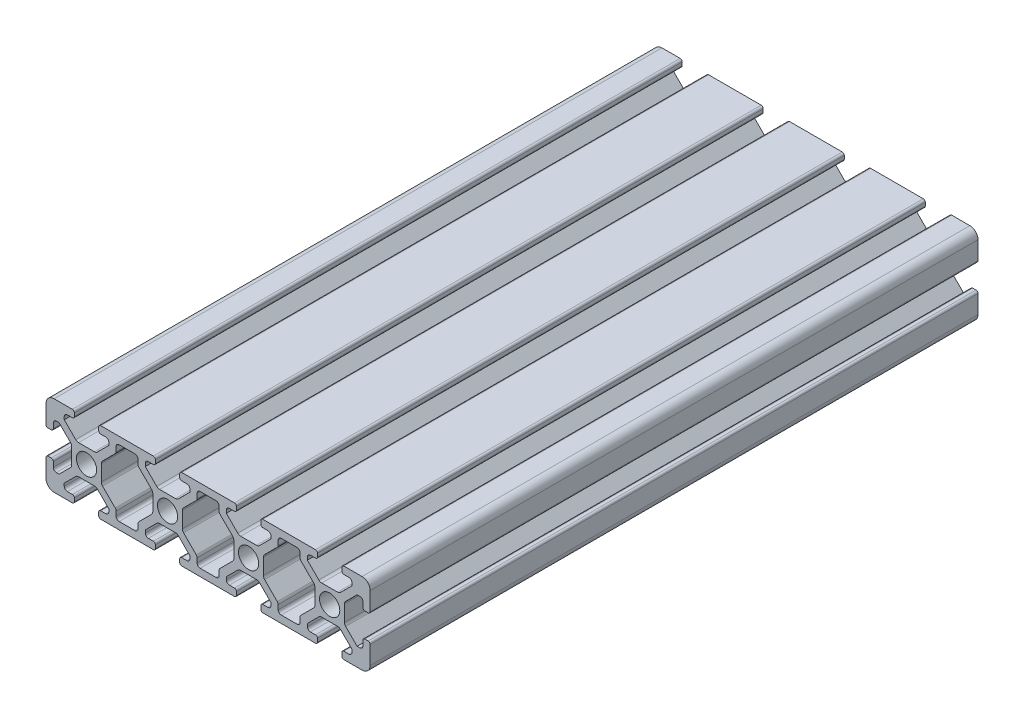
SolidWorks part; units mm, degrees
material "6063-T5"
ref_plane "Front Plane" through (0, 0, 0) normal (0, 0, 1) x (1, 0, 0)
ref_plane "Top Plane" through (0, 0, 0) normal (0, 1, 0) x (1, 0, 0)
ref_plane "Right Plane" through (0, 0, 0) normal (1, 0, 0) x (0, 0, -1)
sketch "Sketch1" plane through (0, 0, 0) normal (0, 0, 1) x (1, 0, 0)
  line L0 (-41.935, 2.3415) -> (-37.435, 2.3415)
  line L1 (36.065, 4.3415) -> (36.065, 8.8415)
  line L2 (34.065, 22.3415) -> (29.565, 22.3415)
  line L3 (-43.935, 20.3415) -> (-43.935, 15.8415)
  line L4 (-10.935, 21.8415) -> (-10.935, 21.0415)
  line L5 (-16.935, 21.8415) -> (-16.935, 21.0415)
  line L6 (-36.935, 21.8415) -> (-36.935, 21.0415)
  line L7 (-30.935, 21.8415) -> (-30.935, 21.0415)
  line L8 (-37.435, 22.3415) -> (-41.935, 22.3415)
  line L9 (9.065, 21.8415) -> (9.065, 21.0415)
  line L10 (3.065, 21.8415) -> (3.065, 21.0415)
  line L11 (29.065, 21.8415) -> (29.065, 21.0415)
  line L12 (23.065, 21.8415) -> (23.065, 21.0415)
  line L13 (-10.935, 3.6415) -> (-10.935, 2.8415)
  line L14 (-16.935, 3.6415) -> (-16.935, 2.8415)
  line L15 (9.065, 3.6415) -> (9.065, 2.8415)
  line L16 (3.065, 3.6415) -> (3.065, 2.8415)
  line L17 (29.065, 3.6415) -> (29.065, 2.8415)
  line L18 (23.065, 3.6415) -> (23.065, 2.8415)
  line L19 (-30.935, 3.6415) -> (-30.935, 2.8415)
  line L20 (-36.935, 3.6415) -> (-36.935, 2.8415)
  line L21 (-30.435, 22.3415) -> (-17.435, 22.3415) construction
  line L22 (-17.435, 22.3415) -> (-30.435, 22.3415)
  line L23 (2.565, 22.3415) -> (-10.435, 22.3415)
  line L24 (22.565, 22.3415) -> (9.565, 22.3415)
  line L25 (29.565, 2.3415) -> (34.065, 2.3415)
  line L26 (9.565, 2.3415) -> (22.565, 2.3415)
  line L27 (-10.435, 2.3415) -> (2.565, 2.3415)
  line L28 (-30.435, 2.3415) -> (-17.435, 2.3415)
  line L29 (35.565, 15.3415) -> (34.765, 15.3415)
  line L30 (35.565, 9.3415) -> (34.765, 9.3415)
  line L31 (-43.435, 15.3415) -> (-42.635, 15.3415)
  line L32 (-43.435, 9.3415) -> (-42.635, 9.3415)
  line L33 (-43.935, 8.8415) -> (-43.935, 4.3415)
  line L34 (36.065, 15.8415) -> (36.065, 20.3415)
  line L35 (-42.135, 15.8415) -> (-42.135, 17.0915)
  line L36 (-38.685, 20.5415) -> (-37.435, 20.5415)
  line L37 (34.265, 17.0915) -> (34.265, 15.8415)
  line L38 (30.815, 4.1415) -> (29.565, 4.1415)
  line L39 (-42.135, 7.5915) -> (-42.135, 8.8415)
  line L40 (-30.435, 20.5415) -> (-29.185, 20.5415)
  line L41 (-37.435, 4.1415) -> (-38.685, 4.1415)
  line L42 (-10.435, 20.5415) -> (-9.185, 20.5415)
  line L43 (-17.435, 4.1415) -> (-18.685, 4.1415)
  line L44 (9.565, 20.5415) -> (10.815, 20.5415)
  line L45 (2.565, 4.1415) -> (1.315, 4.1415)
  line L46 (29.565, 20.5415) -> (30.815, 20.5415)
  line L47 (22.565, 4.1415) -> (21.315, 4.1415)
  line L48 (34.265, 8.8415) -> (34.265, 7.5915)
  line L49 (-31.2649, 16.2843) -> (-28.435, 19.1142)
  line L50 (-31.2649, 8.3986) -> (-28.435, 5.5687)
  line L51 (-11.2649, 16.2843) -> (-8.435, 19.1142)
  line L52 (-9.9921, 15.0116) -> (-6.8546, 18.149)
  line L53 (-16.6051, 16.2843) -> (-19.435, 19.1142)
  line L54 (-21.0153, 18.149) -> (-17.8778, 15.0116)
  line L55 (-16.6051, 8.3986) -> (-19.435, 5.5687)
  line L56 (-21.0153, 6.5339) -> (-17.8778, 9.6714)
  line L57 (3.3949, 16.2843) -> (0.565, 19.1142)
  line L58 (-1.0153, 18.149) -> (2.1222, 15.0116)
  line L59 (3.3949, 8.3986) -> (0.565, 5.5687)
  line L60 (-1.0153, 6.5339) -> (2.1222, 9.6714)
  line L61 (23.3949, 16.2843) -> (20.565, 19.1142)
  line L62 (18.9847, 18.149) -> (22.1222, 15.0116)
  line L63 (23.3949, 8.3986) -> (20.565, 5.5687)
  line L64 (18.9847, 6.5339) -> (22.1222, 9.6714)
  line L65 (-9.9921, 9.6714) -> (-6.8546, 6.5339)
  line L66 (-29.9921, 15.0116) -> (-26.8546, 18.149)
  line L67 (-37.8778, 9.6714) -> (-40.7077, 6.8415)
  line L68 (-36.6051, 8.3986) -> (-39.435, 5.5687)
  line L69 (-36.6051, 16.2843) -> (-39.435, 19.1142)
  line L70 (-11.2649, 8.3986) -> (-8.435, 5.5687)
  line L71 (-29.9921, 9.6714) -> (-26.8546, 6.5339)
  line L72 (8.7351, 16.2843) -> (11.565, 19.1142)
  line L73 (-37.8778, 15.0116) -> (-40.7077, 17.8415)
  line L74 (10.0079, 15.0116) -> (13.1454, 18.149)
  line L75 (10.0079, 9.6714) -> (13.1454, 6.5339)
  line L76 (8.7351, 8.3986) -> (11.565, 5.5687)
  line L77 (28.7351, 16.2843) -> (31.565, 19.1142)
  line L78 (30.0079, 15.0116) -> (32.8378, 17.8415)
  line L79 (30.0079, 9.6714) -> (32.8378, 6.8415)
  line L80 (28.7351, 8.3986) -> (31.565, 5.5687)
  line L81 (-15.898, 15.9915) -> (-11.972, 15.9915)
  line L82 (-25.885, 20.5415) -> (-21.985, 20.5415)
  line L83 (-29.185, 4.1415) -> (-30.435, 4.1415)
  line L84 (-28.435, 19.7915) -> (-28.435, 19.1142)
  line L85 (-9.185, 4.1415) -> (-10.435, 4.1415)
  line L86 (-39.435, 19.7915) -> (-39.435, 19.1142)
  line L87 (10.815, 4.1415) -> (9.565, 4.1415)
  line L88 (-19.435, 19.7915) -> (-19.435, 19.1142)
  line L89 (-18.685, 20.5415) -> (-17.435, 20.5415)
  line L90 (1.315, 20.5415) -> (2.565, 20.5415)
  line L91 (-10.285, 14.3044) -> (-10.285, 10.3785)
  line L92 (-11.972, 8.6915) -> (-15.898, 8.6915)
  line L93 (-17.585, 10.3785) -> (-17.585, 14.3044)
  line L94 (21.315, 20.5415) -> (22.565, 20.5415)
  line L95 (0.565, 19.7915) -> (0.565, 19.1142)
  line L96 (-8.435, 19.7915) -> (-8.435, 19.1142)
  line L97 (-30.285, 14.3044) -> (-30.285, 10.3785)
  line L98 (-31.972, 8.6915) -> (-35.898, 8.6915)
  line L99 (-37.585, 10.3785) -> (-37.585, 14.3044)
  line L100 (-35.898, 15.9915) -> (-31.972, 15.9915)
  line L101 (4.102, 15.9915) -> (8.028, 15.9915)
  line L102 (9.715, 14.3044) -> (9.715, 10.3785)
  line L103 (8.028, 8.6915) -> (4.102, 8.6915)
  line L104 (2.415, 10.3785) -> (2.415, 14.3044)
  line L105 (24.102, 15.9915) -> (28.028, 15.9915)
  line L106 (29.715, 14.3044) -> (29.715, 10.3785)
  line L107 (28.028, 8.6915) -> (24.102, 8.6915)
  line L108 (22.415, 10.3785) -> (22.415, 14.3044)
  line L109 (20.565, 19.7915) -> (20.565, 19.1142)
  line L110 (11.565, 19.7915) -> (11.565, 19.1142)
  line L111 (-39.435, 4.8915) -> (-39.435, 5.5687)
  line L112 (31.565, 19.7915) -> (31.565, 19.1142)
  line L113 (-19.435, 4.8915) -> (-19.435, 5.5687)
  line L114 (-28.435, 4.8915) -> (-28.435, 5.5687)
  line L115 (0.565, 4.8915) -> (0.565, 5.5687)
  line L116 (-8.435, 4.8915) -> (-8.435, 5.5687)
  line L117 (20.565, 4.8915) -> (20.565, 5.5687)
  line L118 (11.565, 4.8915) -> (11.565, 5.5687)
  line L119 (-41.385, 17.8415) -> (-40.7077, 17.8415)
  line L120 (31.565, 4.8915) -> (31.565, 5.5687)
  line L121 (-41.385, 6.8415) -> (-40.7077, 6.8415)
  line L122 (33.515, 17.8415) -> (32.8378, 17.8415)
  line L123 (-26.635, 19.7915) -> (-26.635, 18.6793)
  line L124 (33.515, 6.8415) -> (32.8378, 6.8415)
  line L125 (-21.235, 19.7915) -> (-21.235, 18.6793)
  line L126 (-5.885, 20.5415) -> (-1.985, 20.5415)
  line L127 (-6.635, 19.7915) -> (-6.635, 18.6793)
  line L128 (-1.235, 19.7915) -> (-1.235, 18.6793)
  line L129 (14.115, 20.5415) -> (18.015, 20.5415)
  line L130 (13.365, 19.7915) -> (13.365, 18.6793)
  line L131 (18.765, 19.7915) -> (18.765, 18.6793)
  line L132 (-26.635, 6.0036) -> (-26.635, 4.8915)
  line L133 (-25.885, 4.1415) -> (-21.985, 4.1415)
  line L134 (-21.235, 4.8915) -> (-21.235, 6.0036)
  line L135 (-6.635, 6.0036) -> (-6.635, 4.8915)
  line L136 (-5.885, 4.1415) -> (-1.985, 4.1415)
  line L137 (-1.235, 4.8915) -> (-1.235, 6.0036)
  line L138 (13.365, 6.0036) -> (13.365, 4.8915)
  line L139 (14.115, 4.1415) -> (18.015, 4.1415)
  line L140 (18.765, 4.8915) -> (18.765, 6.0036)
  circle A0 centre (-33.935, 12.3415) radius 2.5
  circle A1 centre (-13.935, 12.3415) radius 2.5
  circle A2 centre (6.065, 12.3415) radius 2.5
  circle A3 centre (26.065, 12.3415) radius 2.5
  arc A4 (34.065, 2.3415) -> (36.065, 4.3415) centre (34.065, 4.3415) ccw
  arc A5 (36.065, 20.3415) -> (34.065, 22.3415) centre (34.065, 20.3415) ccw
  arc A6 (-41.935, 2.3415) -> (-43.935, 4.3415) centre (-41.935, 4.3415) cw
  arc A7 (-41.935, 22.3415) -> (-43.935, 20.3415) centre (-41.935, 20.3415) ccw
  arc A8 (-31.2649, 16.2843) -> (-31.972, 15.9915) centre (-31.972, 16.9915) cw
  arc A9 (-36.6051, 16.2843) -> (-35.898, 15.9915) centre (-35.898, 16.9915) ccw
  arc A10 (-37.8778, 15.0116) -> (-37.585, 14.3044) centre (-38.585, 14.3044) cw
  arc A11 (-37.8778, 9.6714) -> (-37.585, 10.3785) centre (-38.585, 10.3785) ccw
  arc A12 (-36.6051, 8.3986) -> (-35.898, 8.6915) centre (-35.898, 7.6915) cw
  arc A13 (-31.2649, 8.3986) -> (-31.972, 8.6915) centre (-31.972, 7.6915) ccw
  arc A14 (-11.2649, 8.3986) -> (-11.972, 8.6915) centre (-11.972, 7.6915) ccw
  arc A15 (-16.6051, 8.3986) -> (-15.898, 8.6915) centre (-15.898, 7.6915) cw
  arc A16 (-16.6051, 16.2843) -> (-15.898, 15.9915) centre (-15.898, 16.9915) ccw
  arc A17 (-11.2649, 16.2843) -> (-11.972, 15.9915) centre (-11.972, 16.9915) cw
  arc A18 (3.3949, 8.3986) -> (4.102, 8.6915) centre (4.102, 7.6915) cw
  arc A19 (8.7351, 8.3986) -> (8.028, 8.6915) centre (8.028, 7.6915) ccw
  arc A20 (8.7351, 16.2843) -> (8.028, 15.9915) centre (8.028, 16.9915) cw
  arc A21 (3.3949, 16.2843) -> (4.102, 15.9915) centre (4.102, 16.9915) ccw
  arc A22 (28.7351, 16.2843) -> (28.028, 15.9915) centre (28.028, 16.9915) cw
  arc A23 (23.3949, 16.2843) -> (24.102, 15.9915) centre (24.102, 16.9915) ccw
  arc A24 (23.3949, 8.3986) -> (24.102, 8.6915) centre (24.102, 7.6915) cw
  arc A25 (28.7351, 8.3986) -> (28.028, 8.6915) centre (28.028, 7.6915) ccw
  arc A26 (30.0079, 9.6714) -> (29.715, 10.3785) centre (30.715, 10.3785) cw
  arc A27 (30.0079, 15.0116) -> (29.715, 14.3044) centre (30.715, 14.3044) ccw
  arc A28 (22.1222, 9.6714) -> (22.415, 10.3785) centre (21.415, 10.3785) ccw
  arc A29 (22.1222, 15.0116) -> (22.415, 14.3044) centre (21.415, 14.3044) cw
  arc A30 (10.0079, 9.6714) -> (9.715, 10.3785) centre (10.715, 10.3785) cw
  arc A31 (10.0079, 15.0116) -> (9.715, 14.3044) centre (10.715, 14.3044) ccw
  arc A32 (34.265, 17.0915) -> (33.515, 17.8415) centre (33.515, 17.0915) ccw
  arc A33 (31.565, 19.7915) -> (30.815, 20.5415) centre (30.815, 19.7915) ccw
  arc A34 (34.265, 7.5915) -> (33.515, 6.8415) centre (33.515, 7.5915) cw
  arc A35 (31.565, 4.8915) -> (30.815, 4.1415) centre (30.815, 4.8915) cw
  arc A36 (2.1222, 9.6714) -> (2.415, 10.3785) centre (1.415, 10.3785) ccw
  arc A37 (2.1222, 15.0116) -> (2.415, 14.3044) centre (1.415, 14.3044) cw
  arc A38 (-9.9921, 9.6714) -> (-10.285, 10.3785) centre (-9.285, 10.3785) cw
  arc A39 (-9.9921, 15.0116) -> (-10.285, 14.3044) centre (-9.285, 14.3044) ccw
  arc A40 (-29.9921, 15.0116) -> (-30.285, 14.3044) centre (-29.285, 14.3044) ccw
  arc A41 (-29.9921, 9.6714) -> (-30.285, 10.3785) centre (-29.285, 10.3785) cw
  arc A42 (-17.8778, 9.6714) -> (-17.585, 10.3785) centre (-18.585, 10.3785) ccw
  arc A43 (-17.8778, 15.0116) -> (-17.585, 14.3044) centre (-18.585, 14.3044) cw
  arc A44 (21.315, 4.1415) -> (20.565, 4.8915) centre (21.315, 4.8915) cw
  arc A45 (18.015, 4.1415) -> (18.765, 4.8915) centre (18.015, 4.8915) ccw
  arc A46 (13.365, 4.8915) -> (14.115, 4.1415) centre (14.115, 4.8915) ccw
  arc A47 (10.815, 4.1415) -> (11.565, 4.8915) centre (10.815, 4.8915) ccw
  arc A48 (1.315, 4.1415) -> (0.565, 4.8915) centre (1.315, 4.8915) cw
  arc A49 (20.565, 19.7915) -> (21.315, 20.5415) centre (21.315, 19.7915) cw
  arc A50 (18.015, 20.5415) -> (18.765, 19.7915) centre (18.015, 19.7915) cw
  arc A51 (14.115, 20.5415) -> (13.365, 19.7915) centre (14.115, 19.7915) ccw
  arc A52 (9.065, 21.0415) -> (9.565, 20.5415) centre (9.565, 21.0415) ccw
  arc A53 (9.065, 21.8415) -> (9.565, 22.3415) centre (9.565, 21.8415) cw
  arc A54 (23.065, 21.0415) -> (22.565, 20.5415) centre (22.565, 21.0415) cw
  arc A55 (23.065, 21.8415) -> (22.565, 22.3415) centre (22.565, 21.8415) ccw
  arc A56 (29.065, 21.0415) -> (29.565, 20.5415) centre (29.565, 21.0415) ccw
  arc A57 (29.065, 21.8415) -> (29.565, 22.3415) centre (29.565, 21.8415) cw
  arc A58 (34.765, 15.3415) -> (34.265, 15.8415) centre (34.765, 15.8415) cw
  arc A59 (35.565, 15.3415) -> (36.065, 15.8415) centre (35.565, 15.8415) ccw
  arc A60 (34.765, 9.3415) -> (34.265, 8.8415) centre (34.765, 8.8415) ccw
  arc A61 (35.565, 9.3415) -> (36.065, 8.8415) centre (35.565, 8.8415) cw
  arc A62 (29.065, 2.8415) -> (29.565, 2.3415) centre (29.565, 2.8415) ccw
  arc A63 (29.065, 3.6415) -> (29.565, 4.1415) centre (29.565, 3.6415) cw
  arc A64 (23.065, 2.8415) -> (22.565, 2.3415) centre (22.565, 2.8415) cw
  arc A65 (23.065, 3.6415) -> (22.565, 4.1415) centre (22.565, 3.6415) ccw
  arc A66 (9.065, 2.8415) -> (9.565, 2.3415) centre (9.565, 2.8415) ccw
  arc A67 (9.065, 3.6415) -> (9.565, 4.1415) centre (9.565, 3.6415) cw
  arc A68 (3.065, 2.8415) -> (2.565, 2.3415) centre (2.565, 2.8415) cw
  arc A69 (3.065, 3.6415) -> (2.565, 4.1415) centre (2.565, 3.6415) ccw
  arc A70 (-10.935, 2.8415) -> (-10.435, 2.3415) centre (-10.435, 2.8415) ccw
  arc A71 (-10.935, 3.6415) -> (-10.435, 4.1415) centre (-10.435, 3.6415) cw
  arc A72 (-16.935, 2.8415) -> (-17.435, 2.3415) centre (-17.435, 2.8415) cw
  arc A73 (-16.935, 3.6415) -> (-17.435, 4.1415) centre (-17.435, 3.6415) ccw
  arc A74 (3.065, 21.0415) -> (2.565, 20.5415) centre (2.565, 21.0415) cw
  arc A75 (3.065, 21.8415) -> (2.565, 22.3415) centre (2.565, 21.8415) ccw
  arc A76 (-10.935, 21.0415) -> (-10.435, 20.5415) centre (-10.435, 21.0415) ccw
  arc A77 (-10.935, 21.8415) -> (-10.435, 22.3415) centre (-10.435, 21.8415) cw
  arc A78 (-16.935, 21.0415) -> (-17.435, 20.5415) centre (-17.435, 21.0415) cw
  arc A79 (-16.935, 21.8415) -> (-17.435, 22.3415) centre (-17.435, 21.8415) ccw
  arc A80 (-30.935, 21.0415) -> (-30.435, 20.5415) centre (-30.435, 21.0415) ccw
  arc A81 (-30.435, 22.3415) -> (-30.935, 21.8415) centre (-30.435, 21.8415) ccw
  arc A82 (-30.935, 2.8415) -> (-30.435, 2.3415) centre (-30.435, 2.8415) ccw
  arc A83 (-30.935, 3.6415) -> (-30.435, 4.1415) centre (-30.435, 3.6415) cw
  arc A84 (-36.935, 2.8415) -> (-37.435, 2.3415) centre (-37.435, 2.8415) cw
  arc A85 (-36.935, 3.6415) -> (-37.435, 4.1415) centre (-37.435, 3.6415) ccw
  arc A86 (-43.935, 8.8415) -> (-43.435, 9.3415) centre (-43.435, 8.8415) cw
  arc A87 (-42.635, 9.3415) -> (-42.135, 8.8415) centre (-42.635, 8.8415) cw
  arc A88 (-43.935, 15.8415) -> (-43.435, 15.3415) centre (-43.435, 15.8415) ccw
  arc A89 (-42.635, 15.3415) -> (-42.135, 15.8415) centre (-42.635, 15.8415) ccw
  arc A90 (-37.435, 22.3415) -> (-36.935, 21.8415) centre (-37.435, 21.8415) cw
  arc A91 (-36.935, 21.0415) -> (-37.435, 20.5415) centre (-37.435, 21.0415) cw
  arc A92 (11.565, 19.7915) -> (10.815, 20.5415) centre (10.815, 19.7915) ccw
  arc A93 (0.565, 19.7915) -> (1.315, 20.5415) centre (1.315, 19.7915) cw
  arc A94 (-6.635, 4.8915) -> (-5.885, 4.1415) centre (-5.885, 4.8915) ccw
  arc A95 (-5.885, 20.5415) -> (-6.635, 19.7915) centre (-5.885, 19.7915) ccw
  arc A96 (-1.985, 20.5415) -> (-1.235, 19.7915) centre (-1.985, 19.7915) cw
  arc A97 (-1.985, 4.1415) -> (-1.235, 4.8915) centre (-1.985, 4.8915) ccw
  arc A98 (-9.185, 4.1415) -> (-8.435, 4.8915) centre (-9.185, 4.8915) ccw
  arc A99 (-18.685, 4.1415) -> (-19.435, 4.8915) centre (-18.685, 4.8915) cw
  arc A100 (-29.185, 4.1415) -> (-28.435, 4.8915) centre (-29.185, 4.8915) ccw
  arc A101 (-38.685, 4.1415) -> (-39.435, 4.8915) centre (-38.685, 4.8915) cw
  arc A102 (-41.385, 6.8415) -> (-42.135, 7.5915) centre (-41.385, 7.5915) cw
  arc A103 (-42.135, 17.0915) -> (-41.385, 17.8415) centre (-41.385, 17.0915) cw
  arc A104 (-19.435, 19.7915) -> (-18.685, 20.5415) centre (-18.685, 19.7915) cw
  arc A105 (-9.185, 20.5415) -> (-8.435, 19.7915) centre (-9.185, 19.7915) cw
  arc A106 (-21.985, 20.5415) -> (-21.235, 19.7915) centre (-21.985, 19.7915) cw
  arc A107 (-25.885, 20.5415) -> (-26.635, 19.7915) centre (-25.885, 19.7915) ccw
  arc A108 (-28.435, 19.7915) -> (-29.185, 20.5415) centre (-29.185, 19.7915) ccw
  arc A109 (-38.685, 20.5415) -> (-39.435, 19.7915) centre (-38.685, 19.7915) ccw
  arc A110 (18.765, 6.0036) -> (18.9847, 6.5339) centre (19.515, 6.0036) cw
  arc A111 (13.365, 6.0036) -> (13.1454, 6.5339) centre (12.615, 6.0036) ccw
  arc A112 (18.765, 18.6793) -> (18.9847, 18.149) centre (19.515, 18.6793) ccw
  arc A113 (13.365, 18.6793) -> (13.1454, 18.149) centre (12.615, 18.6793) cw
  arc A114 (-1.235, 6.0036) -> (-1.0153, 6.5339) centre (-0.485, 6.0036) cw
  arc A115 (-6.635, 6.0036) -> (-6.8546, 6.5339) centre (-7.385, 6.0036) ccw
  arc A116 (-1.235, 18.6793) -> (-1.0153, 18.149) centre (-0.485, 18.6793) ccw
  arc A117 (-6.635, 18.6793) -> (-6.8546, 18.149) centre (-7.385, 18.6793) cw
  arc A118 (-21.235, 18.6793) -> (-21.0153, 18.149) centre (-20.485, 18.6793) ccw
  arc A119 (-26.635, 18.6793) -> (-26.8546, 18.149) centre (-27.385, 18.6793) cw
  arc A120 (-26.635, 6.0036) -> (-26.8546, 6.5339) centre (-27.385, 6.0036) ccw
  arc A121 (-21.235, 6.0036) -> (-21.0153, 6.5339) centre (-20.485, 6.0036) cw
  arc A122 (-21.985, 4.1415) -> (-21.235, 4.8915) centre (-21.985, 4.8915) ccw
  arc A123 (-26.635, 4.8915) -> (-25.885, 4.1415) centre (-25.885, 4.8915) ccw
extrude "Boss-Extrude1" add sketch "Sketch1" along normal blind 150
